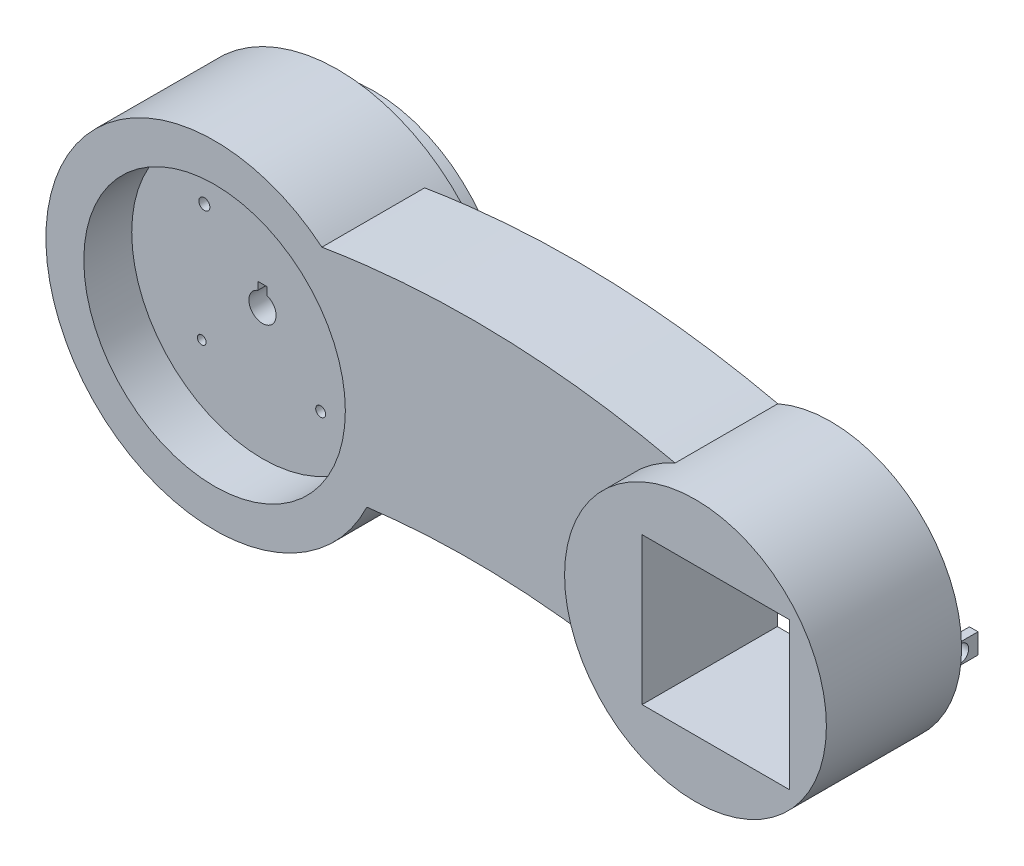
SolidWorks part; units mm, degrees
ref_plane "Front Plane" through (0, 0, 0) normal (0, 0, 1) x (1, 0, 0)
ref_plane "Top Plane" through (0, 0, 0) normal (0, 1, 0) x (1, 0, 0)
ref_plane "Right Plane" through (0, 0, 0) normal (1, 0, 0) x (0, 0, -1)
sketch "Sketch1" plane through (0, 0, 0) normal (0, 0, 1) x (1, 0, 0)
  line L0 (0, 0) -> (300, 0) construction
  line L1 (150, 0) -> (150, 148.1761) construction
  arc A0 (0, 62) -> (0, -62) centre (0, 0) ccw
  arc A1 (300, 62) -> (300, -62) centre (300, 0) cw
  spline S0 degree 2 poles (0, 62) (151.8999, 104.7347) (300, 62) knots 0 0 0 1 1 1
  spline S1 degree 2 poles (0, -62) (150.2796, -14.9575) (300, -62) knots 0 0 0 1 1 1
  dimension "D1" = 300
  dimension "D2" = 124
extrude "Boss-Extrude1" add sketch "Sketch1" along normal blind 60
sketch "Sketch2" plane through (0, 0, 0) normal (0, 0, -1) x (-1, 0, 0)
  circle A0 centre (0, 0) radius 77.225
extrude "Boss-Extrude2" add sketch "Sketch2" along normal blind 33 and the other way up to vertex (60 mm away)
sketch "Sketch3" plane through (0, 0, -33) normal (0, 0, -1) x (-1, 0, 0)
  line L1 (-43, -43) -> (43, -43)
  line L2 (-43, -43) -> (-43, 43)
  line L3 (-43, 43) -> (43, 43)
  line L4 (43, -43) -> (43, 43)
  line L5 (-43, -43) -> (43, 43) construction
  line L6 (-43, 43) -> (43, -43) construction
  point P0 (0, 0)
  dimension "D1" = 86
  dimension "D2" = 86
extrude "Cut-Extrude1" cut sketch "Sketch3" against normal up to vertex
sketch "Sketch5" plane through (0, 0, 60) normal (0, 0, 1) x (1, 0, 0)
  circle A0 centre (300, 0) radius 8.3394
extrude "Cut-Extrude2" cut sketch "Sketch5" against normal blind 32
sketch "Sketch6" plane through (0, 0, 60) normal (0, 0, 1) x (1, 0, 0)
  circle A0 centre (0, 0) radius 98.5577
extrude "Boss-Extrude4" add sketch "Sketch6" against normal blind 72
sketch "Sketch7" plane through (0, 0, 60) normal (0, 0, 1) x (1, 0, 0)
  circle A0 centre (0, 0) radius 76.4117
extrude "Cut-Extrude3" cut sketch "Sketch7" against normal blind 28
sketch "Sketch8" plane through (0, 0, 32) normal (0, 0, 1) x (1, 0, 0)
  line L2 (-2.7187, 7.46) -> (-2.7187, 12.0134)
  line L3 (-2.7187, 12.0134) -> (2.7187, 12.0134)
  line L4 (2.7187, 7.46) -> (2.7187, 12.0134)
  arc A0 (-2.7187, 7.46) -> (2.7187, 7.46) centre (0, 0) ccw
  point P3 (0, 7.94)
  dimension "D1" = 15.88
extrude "Cut-Extrude4" cut sketch "Sketch8" against normal blind 83
fillet "Fillet1" radius 10 1 edges at (77.225, 0, -12)
sketch "Sketch9" plane through (0, 0, 32) normal (0, 0, 1) x (1, 0, 0)
  circle A0 centre (-33.9831, 35.5004) radius 3.2451
  circle A1 centre (35.5004, 33.9831) radius 2.884
  circle A2 centre (-35.5004, -33.9831) radius 2.5503
  circle A3 centre (33.9831, -35.5004) radius 2.892
extrude "Cut-Extrude5" cut sketch "Sketch9" against normal blind 136
sketch "Sketch10" plane through (0, 0, 0) normal (0, 0, -1) x (-1, 0, 0)
  text T0 "KABA" font "Century Gothic" height in points 150
extrude "Boss-Extrude5" add sketch "Sketch10" along normal blind 5
sketch "Sketch11" plane through (0, 0, 0) normal (0, 0, -1) x (-1, 0, 0)
  circle A0 centre (-300, 0) radius 76.4965
extrude "Boss-Extrude6" add sketch "Sketch11" against normal blind 79
sketch "Sketch12" plane through (0, 0, 0) normal (0, 0, -1) x (-1, 0, 0)
  line L1 (-354.811, 43.0908) -> (-268.811, 43.0908)
  line L2 (-354.811, 43.0908) -> (-354.811, -42.9092)
  line L3 (-354.811, -42.9092) -> (-268.811, -42.9092)
  line L4 (-268.811, 43.0908) -> (-268.811, -42.9092)
  dimension "D1" = 86
  dimension "D2" = 86
extrude "Cut-Extrude6" cut sketch "Sketch12" against normal blind 79
sketch "Sketch13" plane through (0, 0, 0) normal (0, 0, -1) x (-1, 0, 0)
  line L1 (-266.5429, -10.9076) -> (-261.5465, -10.9076)
  line L2 (-266.5429, -10.9076) -> (-266.5429, -22.7173)
  line L3 (-266.5429, -22.7173) -> (-261.5465, -22.7173)
  line L4 (-261.5465, -10.9076) -> (-261.5465, -22.7173)
  line L6 (-357.0792, -22.7173) -> (-362.0756, -22.7173)
  line L7 (-362.0756, -10.9076) -> (-362.0756, -22.7173)
  line L8 (-357.0792, -10.9076) -> (-362.0756, -10.9076)
  line L9 (-357.0792, -10.9076) -> (-357.0792, -22.7173)
extrude "Boss-Extrude7" add sketch "Sketch13" along normal blind 24
sketch "Sketch14" plane through (362.0756, 0, 0) normal (1, 0, 0) x (0, 0, -1)
  circle A0 centre (13.529, -16.8124) radius 5.0034
extrude "Cut-Extrude7" cut sketch "Sketch14" against normal blind 110
